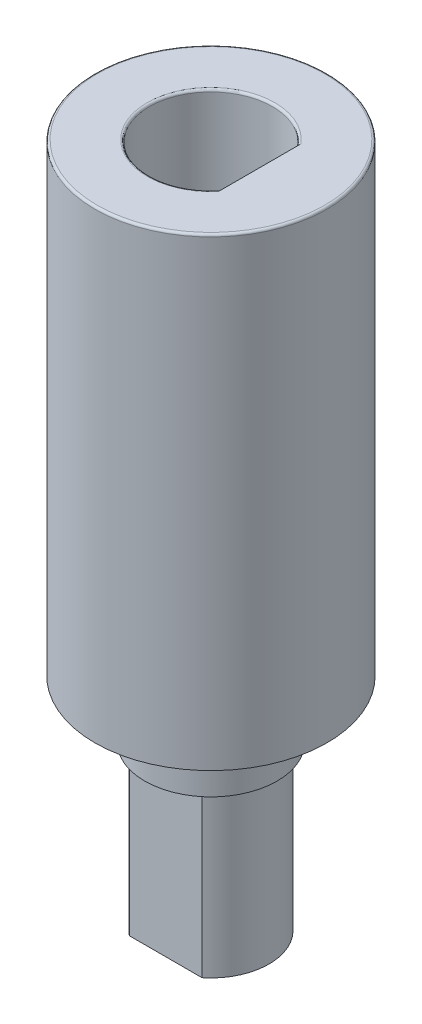
SolidWorks part; units mm, degrees
ref_plane "Front Plane" through (0, 0, 0) normal (0, 0, 1) x (1, 0, 0)
ref_plane "Top Plane" through (0, 0, 0) normal (0, 1, 0) x (1, 0, 0)
ref_plane "Right Plane" through (0, 0, 0) normal (1, 0, 0) x (0, 0, -1)
sketch "Sketch2" plane through (0, 0, 0) normal (0, 1, 0) x (1, 0, 0)
  circle A0 centre (0, 0) radius 5
  dimension "D1" = 10
extrude "Boss-Extrude1" add sketch "Sketch2" along normal blind 20
sketch "Sketch3" plane through (0, 20, 0) normal (0, 1, 0) x (1, 0, 0)
  line L0 (2.1, 1.6163) -> (2.1, -1.6163)
  arc A0 (2.1, 1.6163) -> (2.1, -1.6163) centre (0, 0) ccw
  point P1 (-2.65, 0)
  dimension "D1" = 5.3
  dimension "D2" = 4.75
extrude "Cut-Extrude3" cut sketch "Sketch3" against normal blind 15
sketch "Sketch4" plane through (0, 0, 0) normal (0, -1, 0) x (-1, 0, 0)
  line L1 (1.5644, 1.95) -> (-1.5644, 1.95)
  line L3 (1.5644, -1.95) -> (-1.5644, -1.95)
  line L5 (1.5644, 1.95) -> (-1.5644, -1.95) construction
  line L6 (1.5644, -1.95) -> (-1.5644, 1.95) construction
  arc A0 (1.5644, -1.95) -> (1.5644, 1.95) centre (0, 0) ccw
  arc A1 (-1.5644, -1.95) -> (-1.5644, 1.95) centre (0, 0) cw
  circle A2 centre (0, 0) radius 2.5 construction
  point P0 (0, 0)
  dimension "D1" = 5
  dimension "D2" = 3.9
extrude "Boss-Extrude2" add sketch "Sketch4" along normal blind 9.5
sketch "Sketch6" plane through (0, 0, 0) normal (0, -1, 0) x (1, 0, 0)
  circle A0 centre (0, 0) radius 2.85
  dimension "D1" = 5.7
extrude "Boss-Extrude3" add sketch "Sketch6" along normal blind 2.5
fillet "Fillet3" radius 0.1 2 edges at (0, 20, 5) (-2.65, 20, 0)
